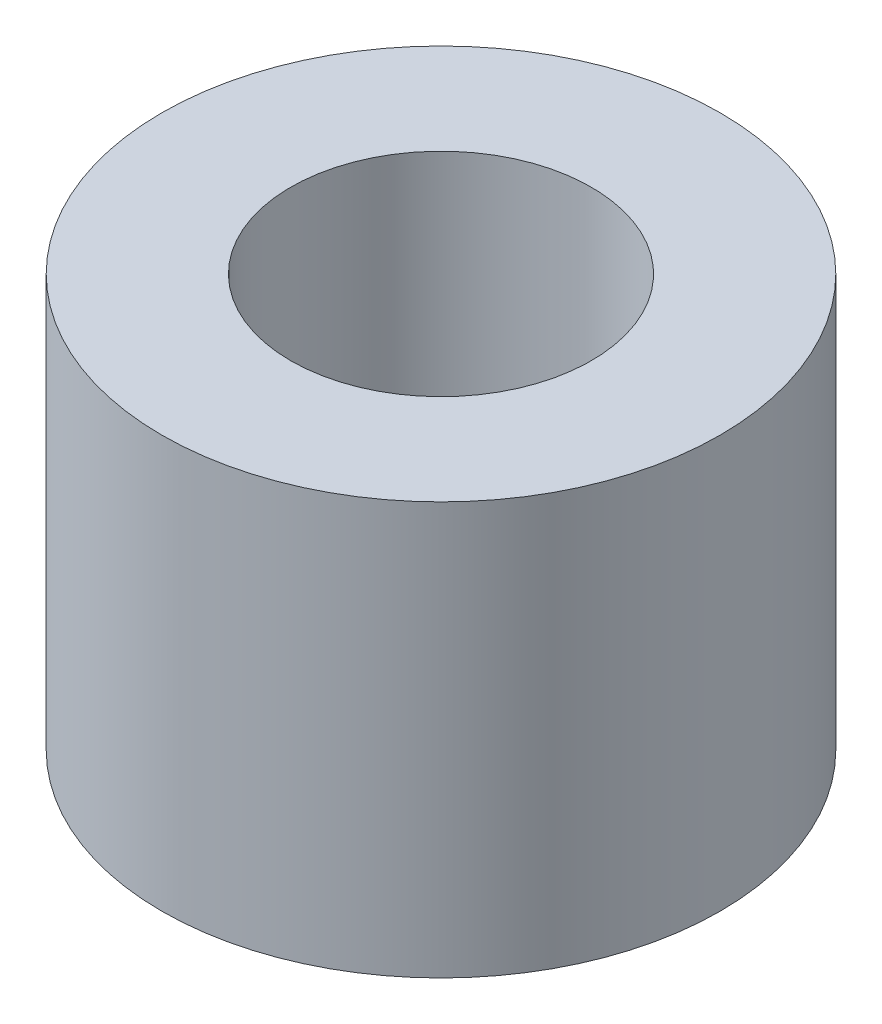
SolidWorks part; units mm, degrees
ref_plane "Front Plane" through (0, 0, 0) normal (0, 0, 1) x (1, 0, 0)
ref_plane "Top Plane" through (0, 0, 0) normal (0, 1, 0) x (1, 0, 0)
ref_plane "Right Plane" through (0, 0, 0) normal (1, 0, 0) x (0, 0, -1)
sketch "Sketch1" plane through (0, 0, 0) normal (0, 1, 0) x (1, 0, 0)
  circle A0 centre (0, 0) radius 3.25
  circle A1 centre (0, 0) radius 1.75
  dimension "D1" = 3.5
  dimension "D2" = 6.5
extrude "Boss-Extrude1" add sketch "Sketch1" along normal blind 4.8
